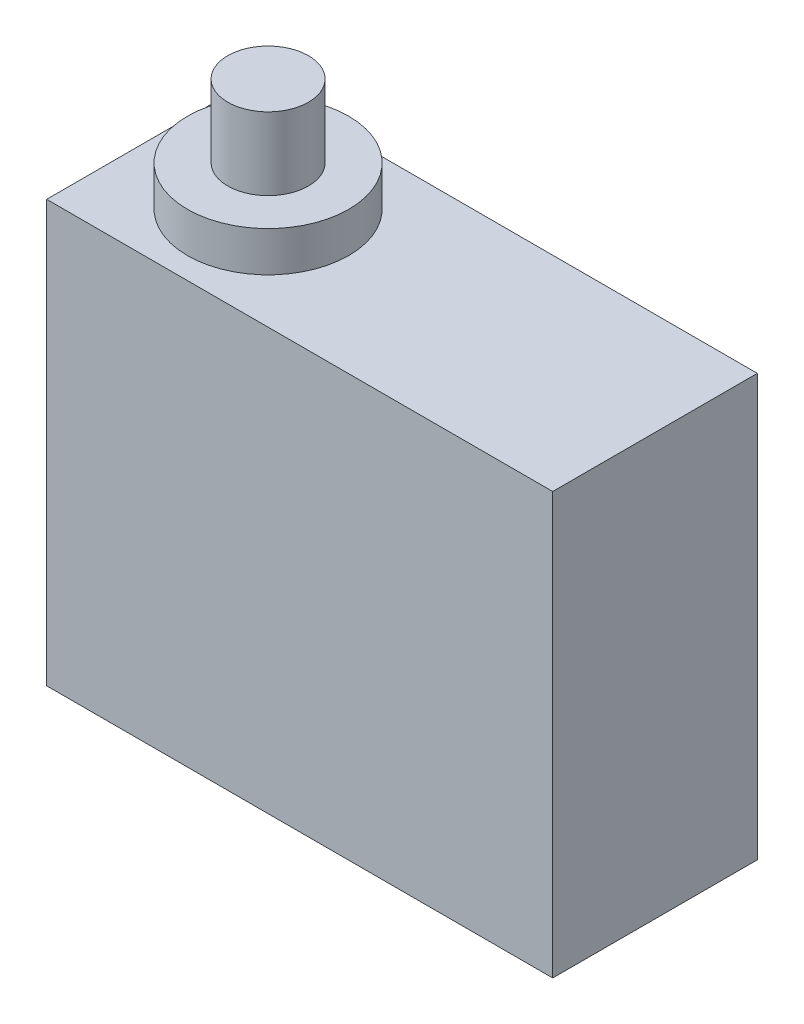
SolidWorks part; units mm, degrees
ref_plane "Front Plane" through (0, 0, 0) normal (0, 0, 1) x (1, 0, 0)
ref_plane "Top Plane" through (0, 0, 0) normal (0, 1, 0) x (1, 0, 0)
ref_plane "Right Plane" through (0, 0, 0) normal (1, 0, 0) x (0, 0, -1)
sketch "Sketch2" plane through (0, 0, 0) normal (0, 0, 1) x (1, 0, 0)
  line L1 (9.41, -7.835) -> (-9.41, -7.835)
  line L2 (9.41, -7.835) -> (9.41, 7.835)
  line L3 (9.41, 7.835) -> (-9.41, 7.835)
  line L4 (-9.41, -7.835) -> (-9.41, 7.835)
  line L5 (9.41, -7.835) -> (-9.41, 7.835) construction
  line L6 (9.41, 7.835) -> (-9.41, -7.835) construction
  point P0 (0, 0)
  dimension "D1" = 18.82
  dimension "D2" = 15.67
extrude "Boss-Extrude1" add sketch "Sketch2" along normal mid plane 7.61
sketch "Sketch3" plane through (0, 7.835, 0) normal (0, 1, 0) x (1, 0, 0)
  line L0 (-9.41, -3.805) -> (-9.41, 3.805) construction
  circle A0 centre (-4.98, 0) radius 3
  point P2 (0, 0)
  point P4 (0, 0)
  dimension "D1" = 6
  dimension "D2" = 4.43
extrude "Boss-Extrude2" add sketch "Sketch3" along normal blind 1.49
sketch "Sketch4" plane through (0, 9.325, 0) normal (0, 1, 0) x (1, 0, 0)
  circle A0 centre (-4.98, 0) radius 1.5
  dimension "D1" = 3
extrude "Boss-Extrude3" add sketch "Sketch4" along normal blind 2.7
